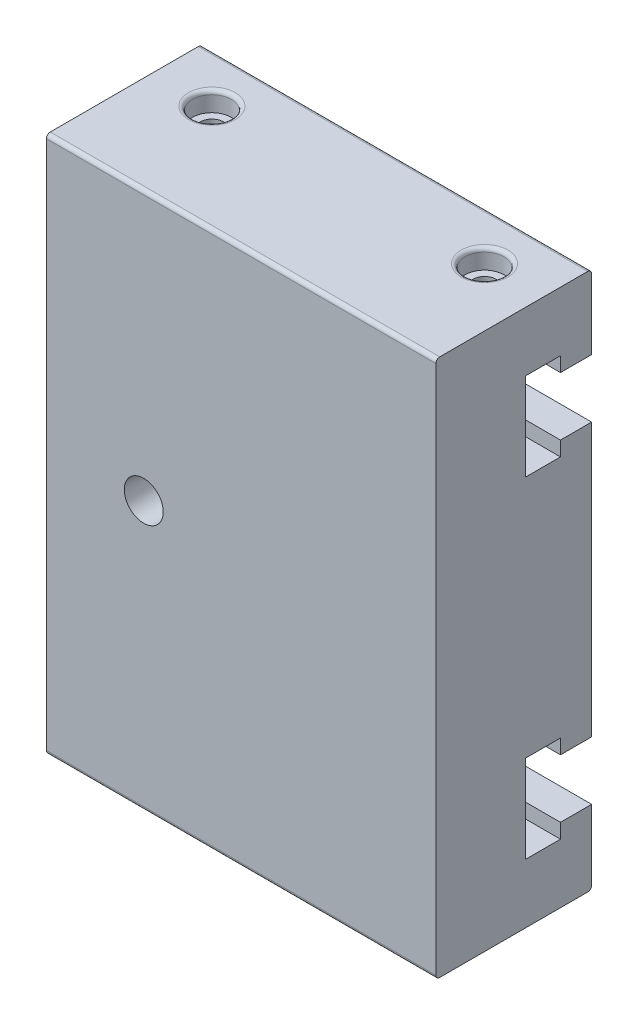
SolidWorks part; units mm, degrees
ref_plane "Ön Düzlem" through (0, 0, 0) normal (0, 0, 1) x (1, 0, 0)
ref_plane "Üst Düzlem" through (0, 0, 0) normal (0, 1, 0) x (1, 0, 0)
ref_plane "Sağ Düzlem" through (0, 0, 0) normal (1, 0, 0) x (0, 0, -1)
sketch "Sketch1" plane through (0, 0, 0) normal (0, 0, 1) x (1, 0, 0)
  line L1 (10, 13.8) -> (-10, 13.8)
  line L2 (10, 13.8) -> (10, -13.8)
  line L3 (10, -13.8) -> (-10, -13.8)
  line L4 (-10, 13.8) -> (-10, -13.8)
  line L5 (10, 13.8) -> (-10, -13.8) construction
  line L6 (10, -13.8) -> (-10, 13.8) construction
  point P0 (0, 0)
  dimension "D1" = 20
  dimension "D2" = 27.6
extrude "Boss-Extrude1" add sketch "Sketch1" along normal mid plane 8
sketch "Sketch3" plane through (0, 0, 4) normal (0, 0, 1) x (1, 0, 0)
  line L0 (-10, 13.8) -> (-10, -13.8) construction
  circle A0 centre (-5, 0) radius 1
  dimension "D1" = 2
  dimension "D2" = 5
extrude "Cut-Extrude2" cut sketch "Sketch3" against normal blind 4
sketch "Sketch4" plane through (10, 0, 0) normal (1, 0, 0) x (0, 0, -1)
  line L0 (4, -13.8) -> (4, 13.8) construction
  line L1 (0.6, 10.75) -> (2.4, 10.75)
  line L2 (0.6, 10.75) -> (0.6, 6.25)
  line L3 (0.6, 6.25) -> (2.4, 6.25)
  line L4 (2.4, 10.75) -> (2.4, 6.25)
  line L5 (0.6, 10.75) -> (2.4, 6.25) construction
  line L6 (0.6, 6.25) -> (2.4, 10.75) construction
  line L7 (2.4, 7) -> (4, 7)
  line L8 (2.4, 7) -> (2.4, 10)
  line L9 (2.4, 10) -> (4, 10)
  line L10 (4, 7) -> (4, 10)
  line L11 (2.4, 7) -> (4, 10) construction
  line L12 (2.4, 10) -> (4, 7) construction
  point P0 (1.5, 8.5)
  point P5 (3.2, 8.5)
  line M1 (4, -13.8) -> (4, 13.8)
  dimension "D1" = 8.5
  dimension "D2" = 4.5
  dimension "D3" = 1.5
  dimension "D4" = 3
  dimension "D5" = 1.8
extrude "Cut-Extrude3" cut sketch "Sketch4" against normal through all contours L9 L4 L7 M1 | L4 L1 L2 L3
sketch "Sketch5" plane through (0, 0, -4) normal (0, 0, -1) x (-1, 0, 0)
  line L0 (10, 7) -> (-10, 7) construction
  circle A0 centre (0, 7) radius 1.5
  dimension "D1" = 3
extrude "Cut-Extrude4" cut sketch "Sketch5" against normal up to surface (3.4 mm away) up to face at (0, 8.5, -0.6)
mirror "Mirror1" about plane through (0, 0, 0) normal (0, 1, 0) of "Cut-Extrude4", "Cut-Extrude3"
sketch "Sketch6" plane through (0, -13.8, 0) normal (0, -1, 0) x (1, 0, 0)
  line L0 (0, 0) -> (0, -4) construction
  line L1 (-10, -4) -> (10, -4) construction
  circle A0 centre (-7, -1.5) radius 1
  circle A1 centre (7, -1.5) radius 1
  dimension "D1" = 2
  dimension "D2" = 1.5
  dimension "D3" = 7
extrude "Cut-Extrude5" cut sketch "Sketch6" against normal blind 1
sketch "Sketch7" plane through (0, -13.8, 0) normal (0, -1, 0) x (1, 0, 0)
  circle A0 centre (-7, -1.5) radius 0.6
  circle A1 centre (7, -1.5) radius 0.6
  dimension "D1" = 1.2
extrude "Cut-Extrude6" cut sketch "Sketch7" against normal through all
fillet "Fillet1" radius 1 4 edges at (-1.5, -7, -3.2) (1.5, -7, -3.2) (1.5, 7, -3.2) (-1.5, 7, -3.2)
mirror "Mirror2" about plane through (0, 0, 0) normal (0, 1, 0) of "Cut-Extrude5"
fillet "Fillet2" radius 0.2 8 edges at (6, 13.8, -1.5) (-6, 13.8, -1.5) (-6, -13.8, -1.5) (6, -13.8, -1.5) (0, -13.8, -4) (0, 13.8, -4) (0, 13.8, 4) (0, -13.8, 4)
